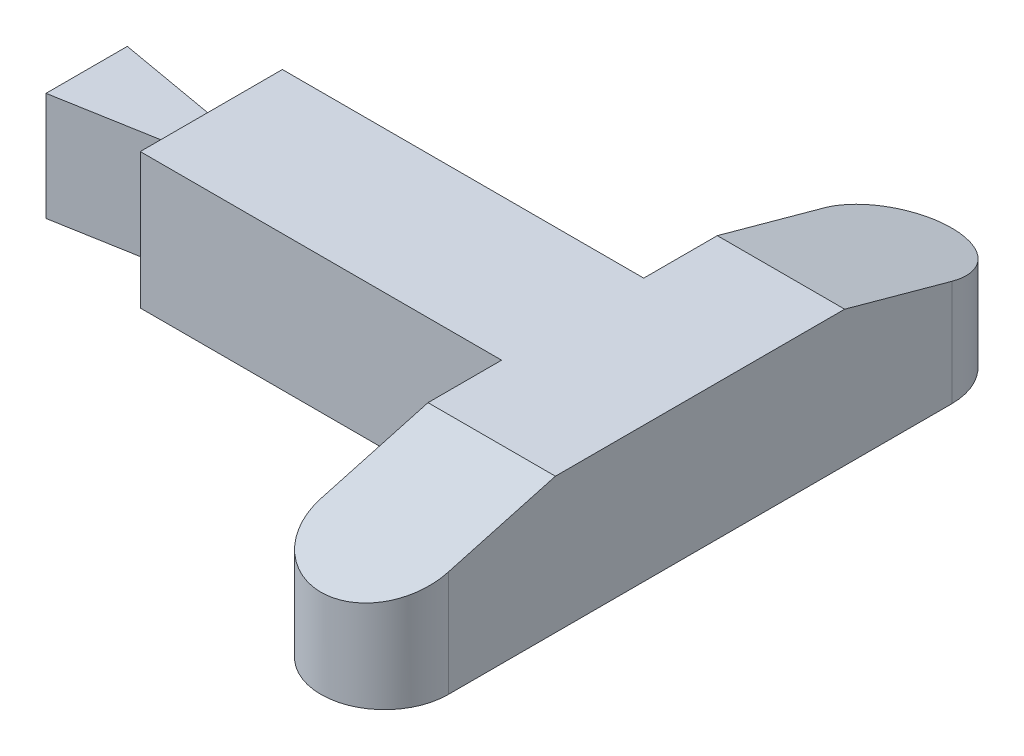
SolidWorks part; units mm, degrees
ref_plane "Front Plane" through (0, 0, 0) normal (0, 0, 1) x (1, 0, 0)
ref_plane "Top Plane" through (0, 0, 0) normal (0, 1, 0) x (1, 0, 0)
ref_plane "Right Plane" through (0, 0, 0) normal (1, 0, 0) x (0, 0, -1)
sketch "Sketch1" plane through (0, 0, 0) normal (0, 1, 0) x (1, 0, 0)
  line L0 (0, 11.43) -> (0, -11.43)
  line L1 (0, 11.43) -> (35.052, 5.2494)
  line L2 (0, -11.43) -> (35.052, -5.2494)
  line L3 (35.052, 5.2494) -> (35.052, 19.9814)
  line L4 (35.052, -5.2494) -> (35.052, -19.9814)
  line L5 (35.052, 5.2494) -> (35.052, -5.2494) construction
  line L6 (0, 0) -> (35.052, 0) construction
  line L7 (35.052, 19.9814) -> (136.652, 19.9814)
  line L8 (35.052, -19.9814) -> (136.652, -19.9814)
  line L9 (136.652, 19.9814) -> (136.652, 70.7814)
  line L10 (136.652, -19.9814) -> (136.652, -70.7814)
  line L12 (172.466, 70.7814) -> (172.466, -70.7814)
  arc A0 (172.466, 70.7814) -> (136.652, 70.7814) centre (154.559, 70.7814) ccw
  arc A1 (172.466, -70.7814) -> (136.652, -70.7814) centre (154.559, -70.7814) cw
  point P3 (0, 0)
  dimension "D1" = 22.86
  dimension "D2" = 35.052
  dimension "D3" = 80
  dimension "D4" = 80
  dimension "D5" = 39.9628
  dimension "D6" = 14.732
  dimension "D7" = 101.6
  dimension "D8" = 101.6
  dimension "D9" = 14.732
  dimension "D10" = 50.8
  dimension "D11" = 35.814
extrude "Boss-Extrude1" add sketch "Sketch1" along normal blind 38.1
sketch "Sketch3" plane through (172.466, 0, 0) normal (1, 0, 0) x (0, 0, -1)
  line L0 (-40.6688, 38.1) -> (-88.6884, 24.9037)
  line L5 (-70.7814, 38.1) -> (70.7814, 38.1) construction
  line L7 (0, 38.1) -> (0, 0) construction
  line L8 (-70.7814, 0) -> (70.7814, 0) construction
  line L9 (-88.6884, 38.1) -> (-88.6884, 0) construction
  dimension "D1" = 49.7998
  dimension "D2" = 15.366
extrude "Cut-Extrude-Thin5" cut sketch "Sketch3" against normal blind 35.814 thin
sketch "Sketch4" plane through (172.466, 0, 0) normal (1, 0, 0) x (0, 0, -1)
  line L0 (-40.6688, 38.1) -> (-88.6884, 24.9037) construction
  line L3 (0, 38.1) -> (0, 0) construction
  line L5 (-40.6688, 38.1) -> (70.7814, 38.1) construction
  line L6 (-70.7814, 0) -> (70.7814, 0) construction
  line L7 (40.6688, 38.1) -> (88.6884, 24.9037)
extrude "Cut-Extrude9" cut sketch "Sketch4" against normal blind 35.814 and the other way through all
sketch "Sketch5" plane through (0, 38.1, 0) normal (0, 1, 0) x (1, 0, 0)
  line L0 (0, -11.43) -> (0, 11.43)
  line L1 (0, -11.43) -> (35.052, -5.2494) construction
  line L2 (0, 11.43) -> (0, -11.43) construction
  line L3 (0, 11.43) -> (0.2105, 11.603)
  line L4 (35.052, 5.2494) -> (35.052, -5.2494)
  line L5 (35.052, -5.2494) -> (0, -11.43)
  line L6 (0.2105, 11.603) -> (35.052, 5.2494)
  dimension "D1" = 79.665
extrude "Cut-Extrude10" cut sketch "Sketch5" against normal blind 7.62
